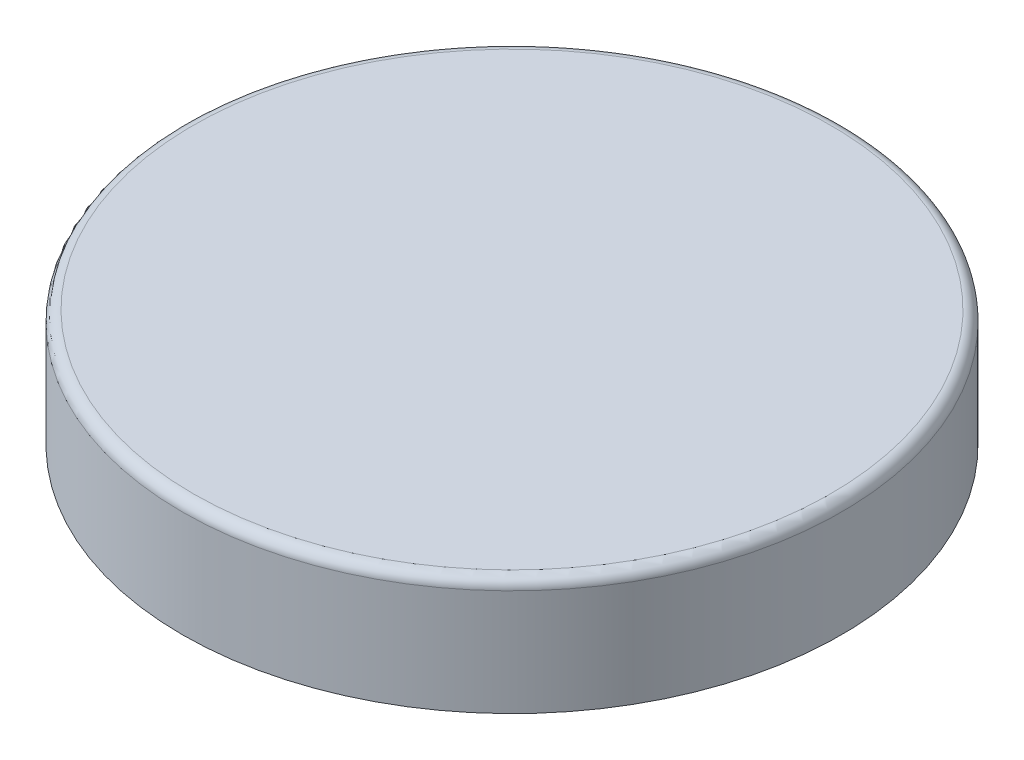
SolidWorks part; units mm, degrees
material "PS Medium/High Flow"
ref_plane "Front Plane" through (0, 0, 0) normal (0, 0, 1) x (1, 0, 0)
ref_plane "Top Plane" through (0, 0, 0) normal (0, 1, 0) x (1, 0, 0)
ref_plane "Right Plane" through (0, 0, 0) normal (1, 0, 0) x (0, 0, -1)
sketch "Sketch1" plane through (0, 0, 0) normal (0, 1, 0) x (1, 0, 0)
  circle A0 centre (0, 0) radius 30
  circle A1 centre (0, 0) radius 31
  dimension "D1" = 60
  dimension "D2" = 1
extrude "Boss-Extrude1" add sketch "Sketch1" along normal blind 10
sketch "Sketch2" plane through (0, 10, 0) normal (0, 1, 0) x (1, 0, 0)
  circle A0 centre (0, 0) radius 31
extrude "Boss-Extrude2" add sketch "Sketch2" along normal blind 1
fillet "Fillet1" radius 1 1 edges at (0, 11, 31)
